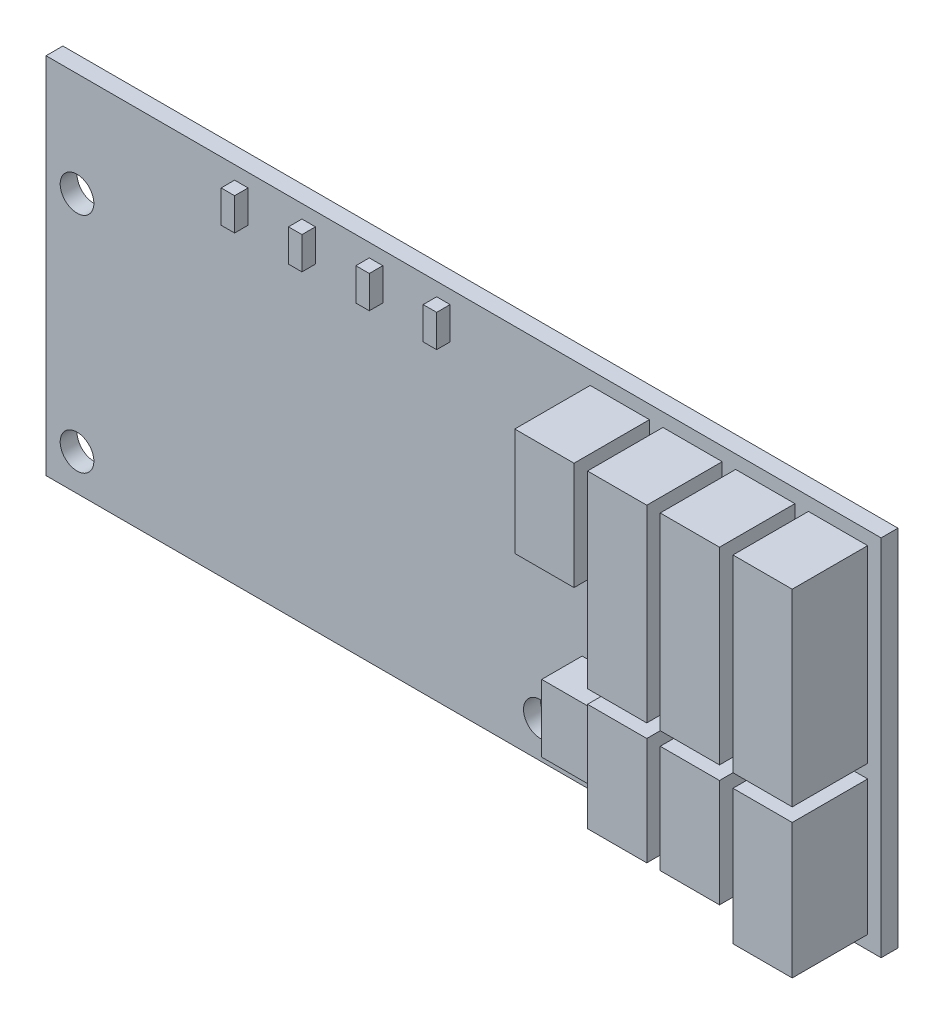
SolidWorks part; units mm, degrees
ref_plane "Front Plane" through (0, 0, 0) normal (0, 0, 1) x (1, 0, 0)
ref_plane "Top Plane" through (0, 0, 0) normal (0, 1, 0) x (1, 0, 0)
ref_plane "Right Plane" through (0, 0, 0) normal (1, 0, 0) x (0, 0, -1)
sketch "Sketch1" plane through (0, 0, 0) normal (0, 0, 1) x (1, 0, 0)
  line L1 (0, 0) -> (78.74, 0)
  line L2 (0, 0) -> (0, 34.29)
  line L3 (0, 34.29) -> (78.74, 34.29)
  line L4 (78.74, 0) -> (78.74, 34.29)
  dimension "D1" = 78.74
  dimension "D2" = 34.29
extrude "Boss-Extrude1" add sketch "Sketch1" along normal blind 1.5875
sketch "Sketch2" plane through (0, 0, 1.5875) normal (0, 0, 1) x (1, 0, 0)
  line L0 (2.921, 3.429) -> (46.609, 3.429) construction
  line L1 (46.609, 3.429) -> (46.609, 24.4856) construction
  line L2 (46.609, 24.4856) -> (2.921, 24.4856) construction
  line L3 (2.921, 24.4856) -> (2.921, 3.429) construction
  line L4 (0, 0) -> (78.74, 0) construction
  line L5 (0, 34.29) -> (0, 0) construction
  circle A0 centre (2.921, 3.429) radius 1.5875
  circle A1 centre (2.921, 24.4856) radius 1.5875
  circle A2 centre (46.609, 24.4856) radius 1.5875
  circle A3 centre (46.609, 3.429) radius 1.5875
  dimension "D1" = 3.175
  dimension "D2" = 3.429
  dimension "D3" = 2.921
  dimension "D4" = 43.688
  dimension "D5" = 21.0566
extrude "Cut-Extrude1" cut sketch "Sketch2" against normal up to next
sketch "Sketch3" plane through (0, 0, 1.5875) normal (0, 0, 1) x (1, 0, 0)
  line L0 (78.74, 34.29) -> (0, 34.29) construction
  line L1 (51.308, 33.02) -> (56.896, 33.02)
  line L2 (51.308, 33.02) -> (51.308, 22.86)
  line L3 (51.308, 22.86) -> (56.896, 22.86)
  line L4 (56.896, 33.02) -> (56.896, 22.86)
  line L5 (58.166, 33.02) -> (63.754, 33.02)
  line L6 (58.166, 33.02) -> (58.166, 15.24)
  line L7 (58.166, 15.24) -> (63.754, 15.24)
  line L8 (63.754, 33.02) -> (63.754, 15.24)
  line L9 (65.024, 33.02) -> (70.612, 33.02)
  line L10 (65.024, 33.02) -> (65.024, 15.24)
  line L11 (65.024, 15.24) -> (70.612, 15.24)
  line L12 (70.612, 33.02) -> (70.612, 15.24)
  line L13 (71.882, 33.02) -> (77.47, 33.02)
  line L14 (71.882, 33.02) -> (71.882, 15.24)
  line L15 (71.882, 15.24) -> (77.47, 15.24)
  line L16 (77.47, 33.02) -> (77.47, 15.24)
  line L17 (58.166, 13.97) -> (63.754, 13.97)
  line L18 (58.166, 13.97) -> (58.166, 3.81)
  line L19 (58.166, 3.81) -> (63.754, 3.81)
  line L20 (63.754, 13.97) -> (63.754, 3.81)
  line L21 (65.024, 13.97) -> (70.612, 13.97)
  line L22 (65.024, 13.97) -> (65.024, 3.81)
  line L23 (65.024, 3.81) -> (70.612, 3.81)
  line L24 (70.612, 13.97) -> (70.612, 3.81)
  line L25 (71.882, 13.97) -> (77.47, 13.97)
  line L26 (71.882, 13.97) -> (71.882, 1.27)
  line L27 (71.882, 1.27) -> (77.47, 1.27)
  line L28 (77.47, 13.97) -> (77.47, 1.27)
  line L29 (78.74, 0) -> (78.74, 34.29) construction
  dimension "D1" = 10.16
  dimension "D2" = 5.588
  dimension "D3" = 12.7
  dimension "D4" = 17.78
  dimension "D5" = 1.27
  dimension "D6" = 1.27
  dimension "D7" = 1.27
  dimension "D8" = 1.27
  dimension "D9" = 1.27
  dimension "D10" = 1.27
  dimension "D11" = 1.27
  dimension "D12" = 1.27
  dimension "D13" = 1.27
extrude "Boss-Extrude2" add sketch "Sketch3" along normal blind 7.112
sketch "Sketch4" plane through (0, 0, 1.5875) normal (0, 0, 1) x (1, 0, 0)
  line L0 (58.166, 13.97) -> (58.166, 3.81) construction
  line L1 (50.546, 10.541) -> (56.896, 10.541)
  line L2 (50.546, 10.541) -> (50.546, 4.191)
  line L3 (50.546, 4.191) -> (56.896, 4.191)
  line L4 (56.896, 10.541) -> (56.896, 4.191)
  line L5 (0, 0) -> (78.74, 0) construction
  dimension "D1" = 6.35
  dimension "D2" = 6.35
  dimension "D3" = 1.27
  dimension "D4" = 4.191
extrude "Boss-Extrude3" add sketch "Sketch4" along normal blind 3.81
ref_plane "Plane1" through (0, 15.875, 0) normal (0, -1, 0) x (-1, 0, 0)
sketch "Sketch5" plane through (0, 15.875, 0) normal (0, -1, 0) x (-1, 0, 0)
  line L0 (-24.13, 9.525) -> (-19.177, 9.525)
  line L1 (-19.177, 9.525) -> (-19.177, 0)
  line L2 (0, 0) -> (-78.74, 0) construction
  line L3 (-19.177, 0) -> (-17.907, 0)
  line L4 (-17.907, 0) -> (-17.907, 8.128)
  line L5 (-17.907, 8.128) -> (-7.493, 8.128)
  line L6 (-7.493, 8.128) -> (-7.493, 0)
  line L7 (-7.493, 0) -> (-6.223, 0)
  line L8 (-6.223, 0) -> (-6.223, 9.525)
  line L9 (-6.223, 9.525) -> (-1.27, 9.525)
  line L10 (-1.27, 9.525) -> (-1.27, 10.16)
  line L11 (-1.27, 10.16) -> (-24.13, 10.16) construction
  line L12 (-24.13, 10.16) -> (-24.13, 9.525)
  line L13 (-12.7, 8.128) -> (-12.7, 10.16) construction
  line L14 (-24.13, 10.16) -> (-18.542, 10.16)
  line L15 (-18.542, 10.16) -> (-18.542, 8.763)
  line L16 (-18.542, 8.763) -> (-6.858, 8.763)
  line L17 (-6.858, 8.763) -> (-6.858, 10.16)
  line L18 (-6.858, 10.16) -> (-1.27, 10.16)
  line L19 (0, -1.5875) -> (0, 0) construction
  dimension "D1" = 10.16
  dimension "D2" = 0.635
  dimension "D3" = 1.27
  dimension "D4" = 10.414
  dimension "D5" = 8.128
  dimension "D6" = 22.86
  dimension "D7" = 0.635
  dimension "D8" = 12.7
  dimension "D9" = 0.635
  dimension "D10" = 0.635
extrude "Boss-Extrude4" add sketch "Sketch5" along normal mid plane 8.001
sketch "Sketch6" plane through (0, 0, 1.5875) normal (0, 0, 1) x (1, 0, 0)
  line L0 (78.74, 0) -> (78.74, 34.29) construction
  line L1 (36.83, 33.02) -> (38.1, 33.02)
  line L2 (36.83, 33.02) -> (36.83, 29.972)
  line L3 (36.83, 29.972) -> (38.1, 29.972)
  line L4 (38.1, 33.02) -> (38.1, 29.972)
  line L5 (30.48, 33.02) -> (31.75, 33.02)
  line L6 (30.48, 33.02) -> (30.48, 29.972)
  line L7 (30.48, 29.972) -> (31.75, 29.972)
  line L8 (31.75, 33.02) -> (31.75, 29.972)
  line L9 (24.13, 33.02) -> (25.4, 33.02)
  line L10 (24.13, 33.02) -> (24.13, 29.972)
  line L11 (24.13, 29.972) -> (25.4, 29.972)
  line L12 (25.4, 33.02) -> (25.4, 29.972)
  line L13 (17.78, 33.02) -> (19.05, 33.02)
  line L14 (17.78, 33.02) -> (17.78, 29.972)
  line L15 (17.78, 29.972) -> (19.05, 29.972)
  line L16 (19.05, 33.02) -> (19.05, 29.972)
  line L17 (78.74, 34.29) -> (0, 34.29) construction
  dimension "D1" = 3.048
  dimension "D2" = 1.27
  dimension "D3" = 5.08
  dimension "D4" = 5.08
  dimension "D5" = 5.08
  dimension "D6" = 40.64
  dimension "D7" = 1.27
extrude "Boss-Extrude5" add sketch "Sketch6" along normal blind 1.27
